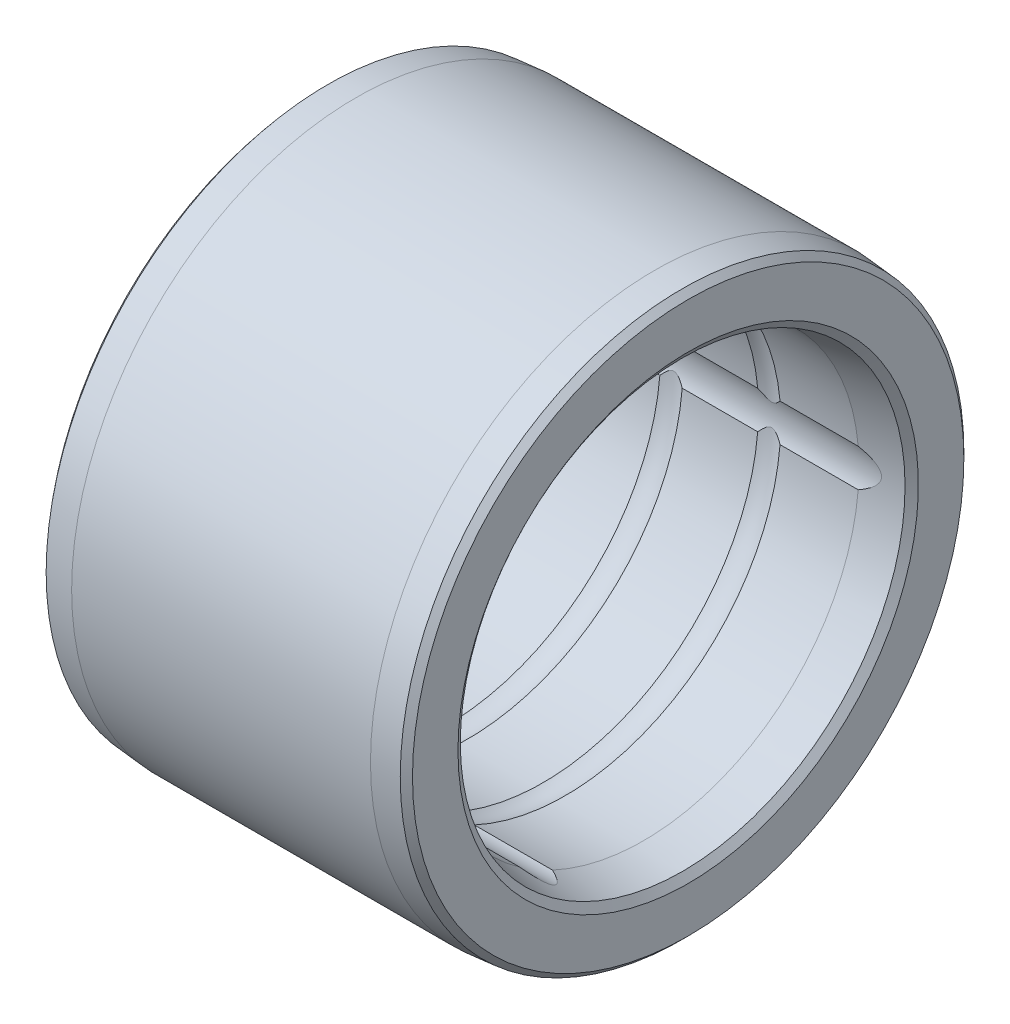
SolidWorks part; units mm, degrees
material "PB01 (C90710) Bronze"
ref_plane "Front Plane" through (0, 0, 0) normal (0, 0, 1) x (1, 0, 0)
ref_plane "Top Plane" through (0, 0, 0) normal (0, 1, 0) x (1, 0, 0)
ref_plane "Right Plane" through (0, 0, 0) normal (1, 0, 0) x (0, 0, -1)
sketch "Sketch1" plane through (0, 0, 0) normal (0, 0, 1) x (1, 0, 0)
  line L0 (0, 10) -> (0, 12.5938)
  line L1 (1.5, 12.725) -> (14.88, 12.725)
  line L2 (16.38, 12.5938) -> (16.38, 10)
  line L3 (16.38, 10) -> (14.38, 9.65)
  line L4 (14.38, 9.65) -> (10.88, 9.65)
  line L5 (2, 9.65) -> (0, 10)
  line L6 (-2.4305, 0) -> (18.5929, 0) construction
  line L7 (1.5, 12.725) -> (0, 12.5938)
  line L8 (14.88, 12.725) -> (16.38, 12.5938)
  line L9 (6, 9.8919) -> (6, 9.0817) construction
  line L10 (5.5, 9.65) -> (2, 9.65)
  line L11 (10.38, 9.8919) -> (10.38, 9.0817) construction
  line L12 (9.88, 9.65) -> (6.5, 9.65)
  arc A0 (5.5, 9.65) -> (6.5, 9.65) centre (6, 8.45) cw
  arc A1 (9.88, 9.65) -> (10.88, 9.65) centre (10.38, 8.45) cw
  dimension "D11" = 1.3
  dimension "D12" = 6
  dimension "D14" = 19.3
  dimension "D1" = 16.38
  dimension "D2" = 25.45
  dimension "D3" = 0.1
  dimension "D4" = 20
  dimension "D5" = 2
  dimension "D6" = 2
  dimension "D7" = 1.5
  dimension "D8" = 1.5
  dimension "D9" = 5
  dimension "D10" = 5
  dimension "D13" = 6
revolve "Revolve1" add sketch "Sketch1" angle 360 about L6
chamfer "ID Chamfer" distance 0.25 angle 45 2 edges at (0, 0, 10) (16.38, 0, 10)
chamfer "OD Chamfer" distance 0.25 angle 45 2 edges at (0, 0, 12.5938) (16.38, 0, 12.5938)
sketch "Sketch2" plane through (0, 0, 0) normal (1, 0, 0) x (0, 0, -1)
  line L0 (-7.8503, 13.5971) -> (-3.2371, 5.6068) construction
  line L1 (0, 0) -> (-4.9841, 0) construction
  arc A0 (-4.0752, 8.7473) -> (-5.5378, 7.9029) centre (-3.9, 6.755) ccw
  circle A2 centre (0, 0) radius 9.65 construction
  arc A3 (-4.0752, 8.7473) -> (-5.5378, 7.9029) centre (0, 0) ccw
  dimension "D1" = 0.15
  dimension "D3" = 60
  dimension "D2" = 2
extrude "Bore Slot" cut sketch "Sketch2" along normal through all
pattern_circular "CirPattern1" count 3 over 360 about axis through (0, 0, 0) along (1, 0, 0) of "Bore Slot"
